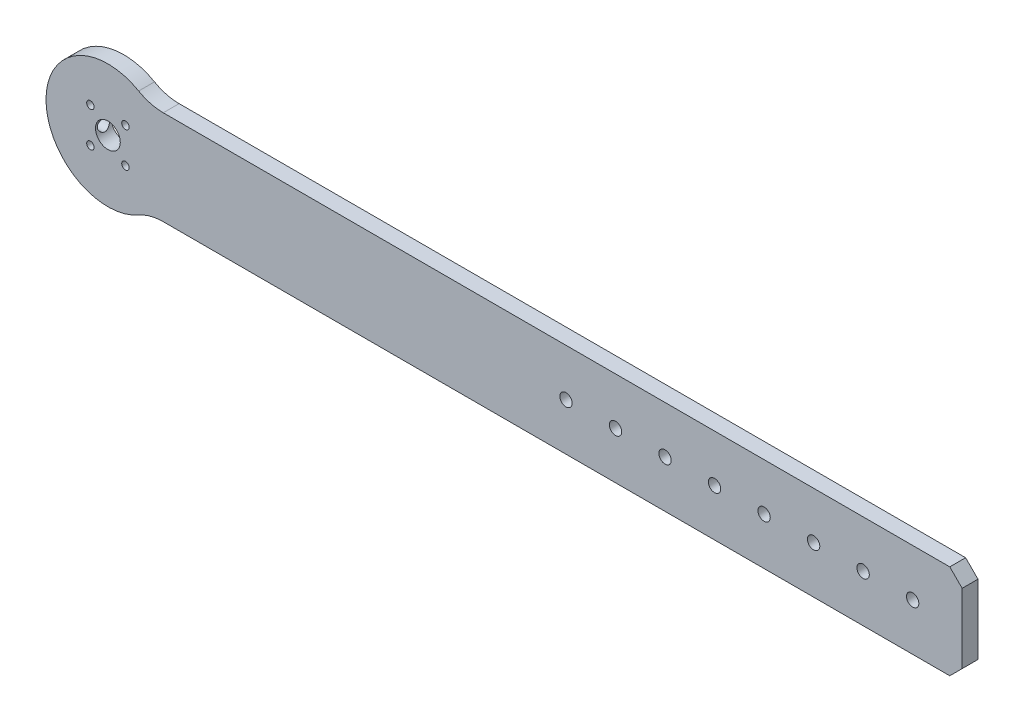
SolidWorks part; units mm, degrees
material "7075-T6, Plate (SS)"
ref_plane "Front Plane" through (0, 0, 0) normal (0, 0, 1) x (1, 0, 0)
ref_plane "Top Plane" through (0, 0, 0) normal (0, 1, 0) x (1, 0, 0)
ref_plane "Right Plane" through (0, 0, 0) normal (1, 0, 0) x (0, 0, -1)
sketch "Sketch1" plane through (0, 0, 0) normal (0, 0, 1) x (1, 0, 0)
  line L0 (0, 0) -> (345, 0) construction
  line L1 (0, 0) -> (-25, 0) construction
  line L2 (345, 19.05) -> (16.1894, 19.05)
  line L3 (345, 19.05) -> (345, -19.05)
  line L4 (345, -19.05) -> (16.1894, -19.05)
  line L6 (0, 0) -> (0, 25) construction
  line L7 (0, 0) -> (7.0711, 7.0711) construction
  arc A0 (16.1894, 19.05) -> (16.1894, -19.05) centre (0, 0) ccw
  circle A1 centre (0, 0) radius 10 construction
  circle A2 centre (7.0711, 7.0711) radius 1.5
  circle A3 centre (7.0711, -7.0711) radius 1.5
  circle A4 centre (-7.0711, -7.0711) radius 1.5
  circle A5 centre (-7.0711, 7.0711) radius 1.5
  circle A6 centre (325, 0) radius 2.5
  circle A7 centre (305, 0) radius 2.5
  circle A8 centre (285, 0) radius 2.5
  circle A9 centre (265, 0) radius 2.5
  circle A10 centre (245, 0) radius 2.5
  circle A11 centre (225, 0) radius 2.5
  circle A12 centre (205, 0) radius 2.5
  circle A13 centre (185, 0) radius 2.5
  circle A14 centre (0, 0) radius 5
  point P21 (0, 0)
  dimension "D1" = 50
  dimension "D4" = 20
  dimension "D6" = 3
  dimension "D8" = 5
  dimension "D12" = 10
  dimension "D2" = 38.1
  dimension "D3" = 370
  dimension "D5" = 45
  dimension "D9" = 20
  dimension "D11" = 20
  dimension "D10" = 8
  dimension "D7" = 4
extrude "Boss-Extrude1" add sketch "Sketch1" along normal mid plane 6.4
sketch "Sketch4" plane through (0, 0, 0) normal (1, 0, 0) x (0, 0, -1)
  circle A0 centre (0, 0) radius 2.5
  dimension "D1" = 5
extrude "Cut-Extrude1" cut sketch "Sketch4" against normal blind 32.4 contours A0
fillet "Fillet1" radius 20 2 edges at (16.1894, -19.05, 0) (16.1894, 19.05, 0)
chamfer "Chamfer1" distance 5 angle 45 2 edges at (345, -19.05, 0) (345, 19.05, 0)
